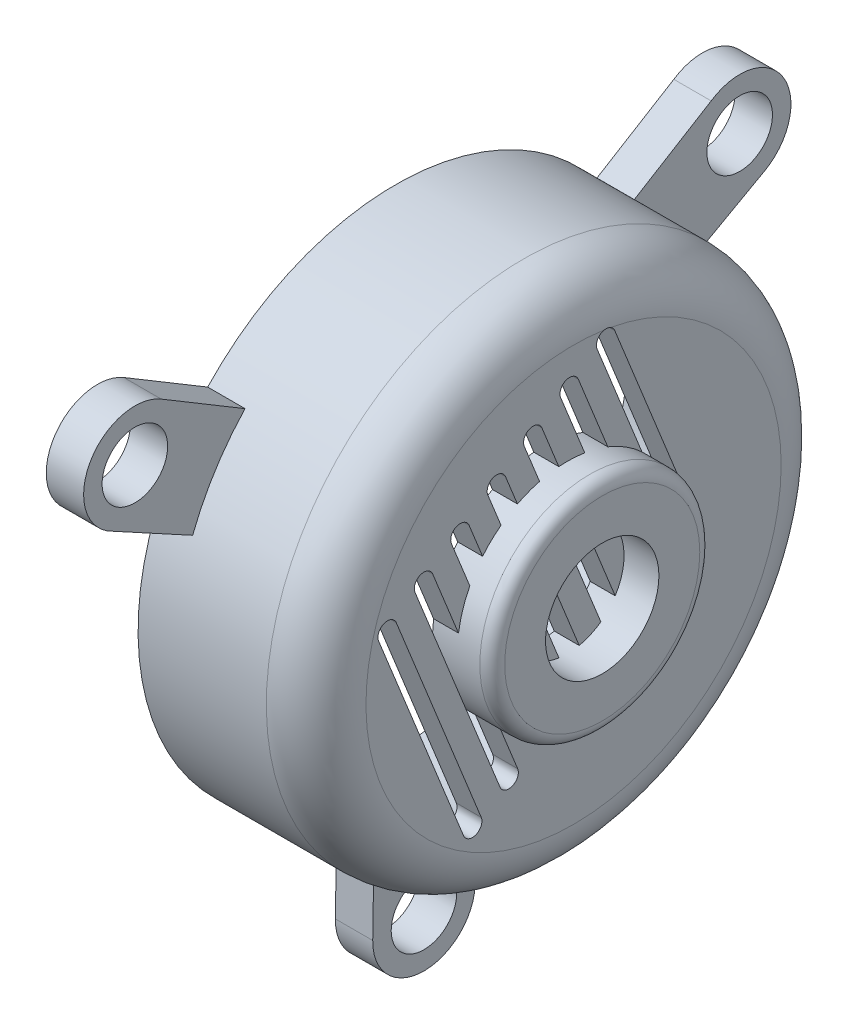
SolidWorks part; units mm, degrees
ref_plane "Front Plane" through (0, 0, 0) normal (0, 0, 1) x (1, 0, 0)
ref_plane "Top Plane" through (0, 0, 0) normal (0, 1, 0) x (1, 0, 0)
ref_plane "Right Plane" through (0, 0, 0) normal (1, 0, 0) x (0, 0, -1)
sketch "Sketch1" plane through (0, 0, 0) normal (1, 0, 0) x (0, 0, -1)
  circle A0 centre (1.2611, 0) radius 52.5081
extrude "Boss-Extrude1" add sketch "Sketch1" along normal blind 36.322
fillet "Fillet1" radius 10.16 1 edges at (36.322, 0, -53.7692)
shell "Shell1" thickness 5.08
sketch "Sketch2" plane through (36.322, 0, 0) normal (1, 0, 0) x (0, 0, -1)
  line L0 (-36.7062, 10.6611) -> (-19.3733, -32.396) construction
  line L1 (-34.9044, 11.3864) -> (-17.5715, -31.6707)
  line L2 (-38.508, 9.9358) -> (-21.1751, -33.1213)
  arc A0 (-34.9044, 11.3864) -> (-38.508, 9.9358) centre (-36.7062, 10.6611) ccw
  arc A1 (-21.1751, -33.1213) -> (-17.5715, -31.6707) centre (-19.3733, -32.396) ccw
  point P2 (-28.0398, -10.8674)
extrude "Cut-Extrude1" cut sketch "Sketch2" against normal blind 8.89
sketch "Sketch4" plane through (36.322, 0, 0) normal (1, 0, 0) x (0, 0, -1)
  line L0 (38.8157, 25.5179) -> (0, 0)
pattern_linear "LPattern1" count 7 spacing 8.89 along (0, 0.5493, -0.8356) of "Cut-Extrude1"
sketch "Sketch6" plane through (36.322, 0, 0) normal (1, 0, 0) x (0, 0, -1)
  circle A0 centre (0, 0) radius 22.4387
  circle A1 centre (0, 0) radius 11.5622
extrude "Boss-Extrude2" add sketch "Sketch6" along normal blind 7.112 and the other way blind 5.08
fillet "Fillet2" radius 2.54 1 edges at (43.434, 0, -22.4387)
sketch "Sketch7" plane through (0, 0, 0) normal (-1, 0, 0) x (0, 0, 1)
  line L5 (-68.9348, 24.9107) -> (-51.5151, 15.2195)
  line L9 (-58.0357, 42.7342) -> (-42.108, 32.9944)
  line L10 (-51.5151, 15.2195) -> (-42.108, 32.9944)
  arc A4 (-58.0357, 42.7342) -> (-68.9348, 24.9107) centre (-63.852, 34.0467) ccw
  circle A5 centre (-63.852, 34.0467) radius 6.6888
  circle A6 centre (-1.2611, 0) radius 52.5081 construction
extrude "Boss-Extrude3" add sketch "Sketch7" against normal blind 7.62
pattern_circular "CirPattern4" count 3 every 120 about axis through (0, 0, -1.2611) along (1, 0, 0) of "Boss-Extrude3"
